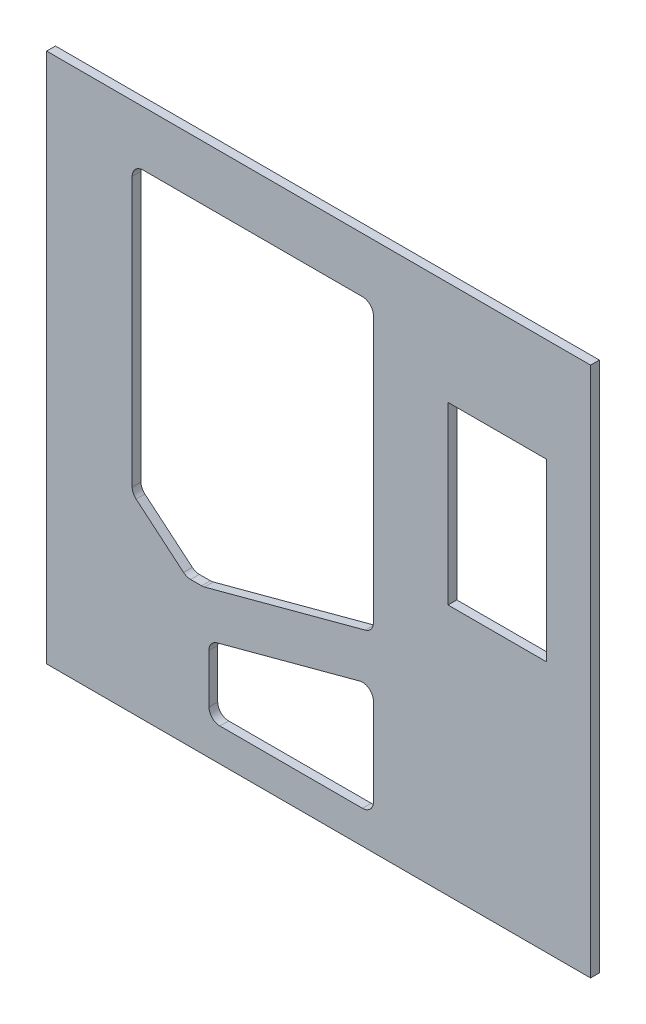
SolidWorks part; units mm, degrees
ref_plane "Front Plane" through (0, 0, 0) normal (0, 0, 1) x (1, 0, 0)
ref_plane "Top Plane" through (0, 0, 0) normal (0, 1, 0) x (1, 0, 0)
ref_plane "Right Plane" through (0, 0, 0) normal (1, 0, 0) x (0, 0, -1)
sketch "Sketch1" plane through (0, 0, 0) normal (0, 0, 1) x (1, 0, 0)
  line L1 (-248, -242) -> (248, -242)
  line L2 (-248, -242) -> (-248, 242)
  line L3 (-248, 242) -> (248, 242)
  line L4 (248, -242) -> (248, 242)
  line L5 (-248, -242) -> (248, 242) construction
  line L6 (-248, 242) -> (248, -242) construction
  point P0 (0, 0)
  dimension "D1" = 496
  dimension "D2" = 484
extrude "Boss-Extrude1" add sketch "Sketch1" along normal blind 8
sketch "Sketch2" plane through (0, 0, 8) normal (0, 0, 1) x (1, 0, 0)
  line L0 (50, -68) -> (-105.382, -109.6345)
  line L1 (50, -68) -> (-170, -68)
  line L2 (50, -68) -> (50, 192)
  line L3 (50, 192) -> (-170, 192)
  line L4 (-170, -68) -> (-170, 192)
  line L5 (50, -68) -> (-170, 192) construction
  line L6 (50, 192) -> (-170, -68) construction
  line L7 (-105.382, -109.6345) -> (-120.382, -109.6345)
  line L8 (-120.382, -109.6345) -> (-170, -68)
  line L9 (248, 242) -> (-248, 242) construction
  line L10 (-248, 242) -> (-248, -242) construction
  line L11 (248, 242) -> (-248, 242)
  point P0 (-60, 62)
  dimension "D1" = 220
  dimension "D2" = 260
  dimension "D3" = 40
  dimension "D4" = 15
  dimension "D5" = 78
  dimension "D6" = 15
  dimension "D7" = 50
extrude "Cut-Extrude1" cut sketch "Sketch2" against normal through all contours L4 L1 L2 L3 | L8 L7 L0 L1
sketch "Sketch3" plane through (0, 0, 8) normal (0, 0, 1) x (1, 0, 0)
  line L1 (50, -109.411) -> (50, -212)
  line L2 (60.3528, -106.637) -> (-95.0292, -148.2715)
  line L3 (50, -109.411) -> (-100, -149.6034)
  line L4 (-248, -242) -> (248, -242) construction
  line L5 (-100, -149.6034) -> (-100, -212)
  line L6 (-100, -212) -> (50, -212)
  dimension "D2" = 30
  dimension "D3" = 150
  dimension "D4" = 0
  dimension "D1" = 40
extrude "Cut-Extrude2" cut sketch "Sketch3" against normal through all
fillet "Fillet1" radius 10 4 edges at (-100, -212, 4) (-100, -149.6034, 4) (50, -109.411, 4) (50, -212, 4)
fillet "Fillet2" radius 10 6 edges at (-170, 192, 4) (50, 192, 4) (50, -68, 4) (-105.382, -109.6345, 4) (-120.382, -109.6345, 4) (-170, -68, 4)
sketch "Sketch4" plane through (0, 0, 8) normal (0, 0, 1) x (1, 0, 0)
  line L8 (118, -12.4322) -> (208, -12.4322)
  line L9 (118, 147.5678) -> (118, -12.4322)
  line L10 (208, 147.5678) -> (118, 147.5678)
  line L11 (208, -12.4322) -> (208, 147.5678)
  line L12 (118, -12.4322) -> (208, -12.4322)
  line L13 (118, 147.5678) -> (118, -12.4322)
  line L14 (208, 147.5678) -> (118, 147.5678)
  line L15 (208, -12.4322) -> (208, 147.5678)
  dimension "D1" = 10
extrude "Cut-Extrude3" cut sketch "Sketch4" against normal up to next contours L13 L12 L15 L14
